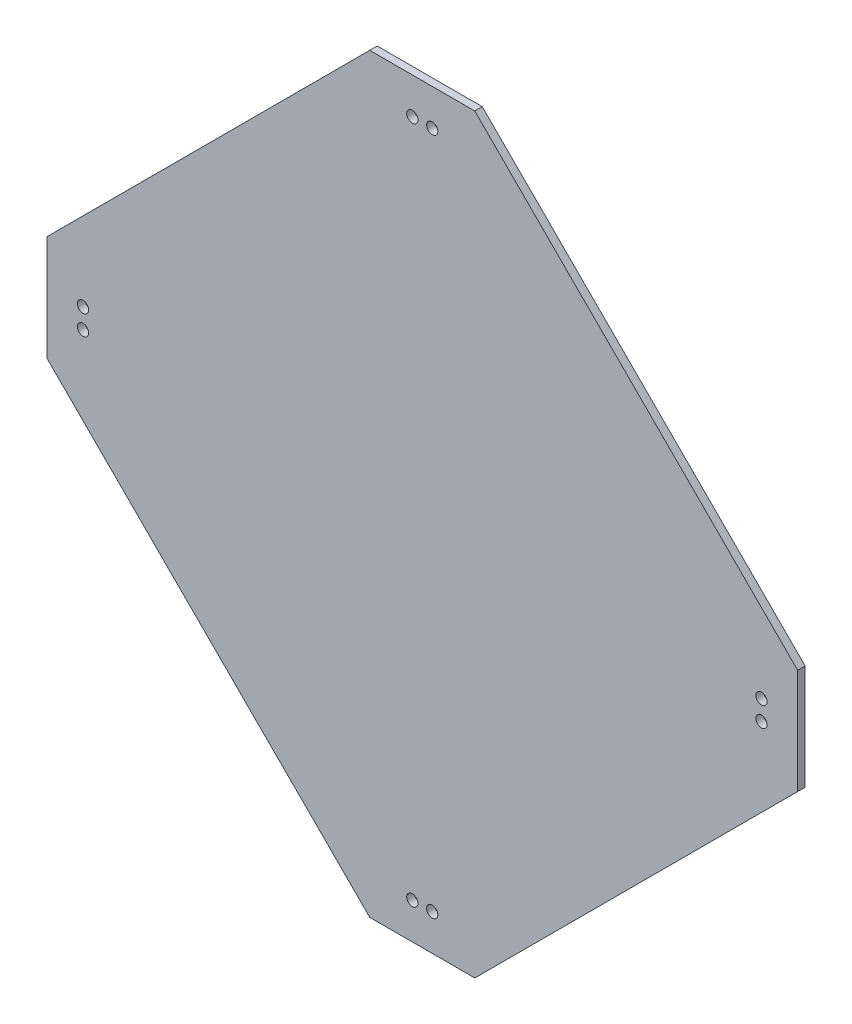
SolidWorks part; units mm, degrees
material "1060 Alloy"
ref_plane "Front Plane" through (0, 0, 0) normal (0, 0, 1) x (1, 0, 0)
ref_plane "Top Plane" through (0, 0, 0) normal (0, 1, 0) x (1, 0, 0)
ref_plane "Right Plane" through (0, 0, 0) normal (1, 0, 0) x (0, 0, -1)
sketch "Sketch2" plane through (54.9511, -12.9282, 0) normal (0, 0, 1) x (1, 0, 0)
  line L1 (150.3463, -129.3158) -> (150.3463, -171.3769)
  line L3 (-21.0306, 0) -> (21.0306, 0)
  line L4 (21.0306, 0) -> (150.3463, -129.3158)
  line L5 (150.3463, -171.3769) -> (85.6884, -236.0347)
  line L6 (85.6884, -236.0347) -> (-85.6884, -64.6579)
  line L7 (-85.6884, -64.6579) -> (-21.0306, 0)
  circle A1 centre (-3.9799, -14.5) radius 2.25
  circle A3 centre (3.9799, -14.5) radius 2.25
  circle A5 centre (135.8463, -154.3263) radius 2.25
  circle A7 centre (135.8463, -146.3664) radius 2.25
extrude "Boss-Extrude1" add sketch "Sketch2" along normal blind 3
mirror "Mirror1" about plane through (140.6395, -248.9629, 3) normal (0.7071, 0.7071, 0) of bodies 101
